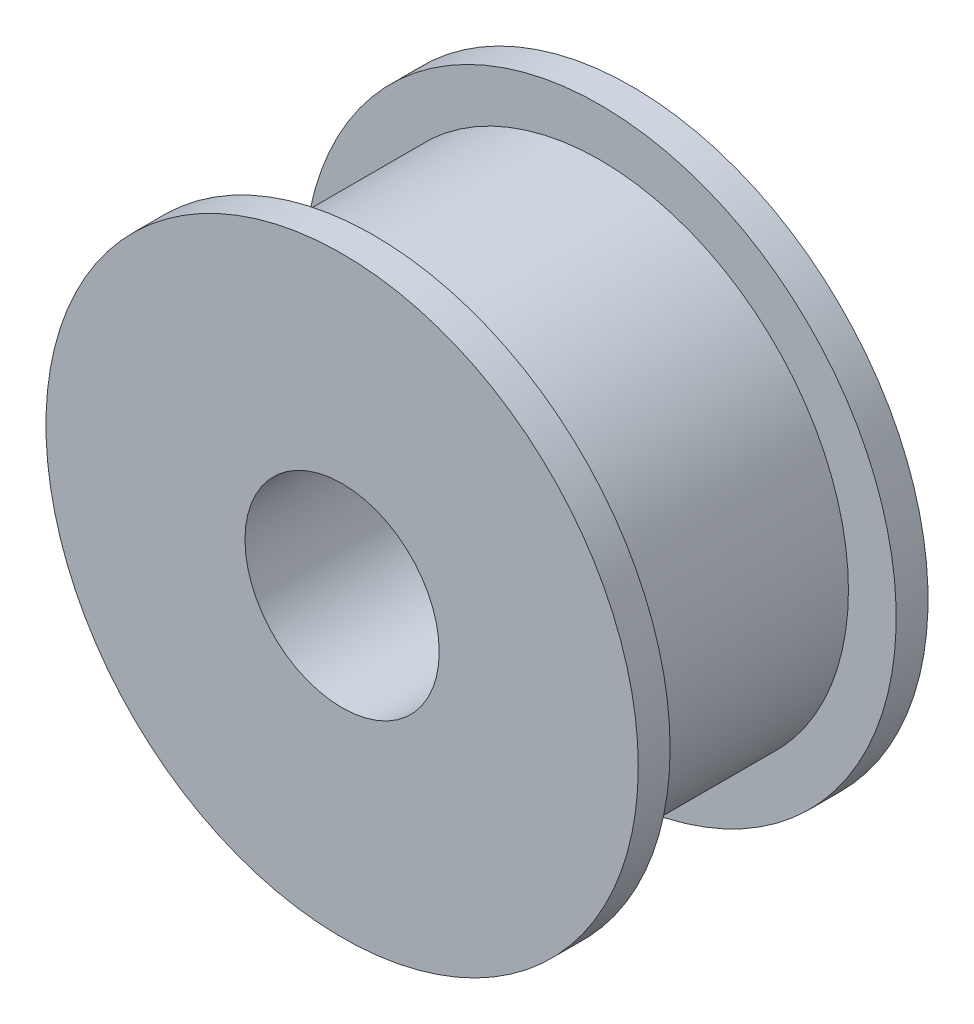
SolidWorks part; units mm, degrees
ref_plane "Plano frontal" through (0, 0, 0) normal (0, 0, 1) x (1, 0, 0)
ref_plane "Plano superior" through (0, 0, 0) normal (0, 1, 0) x (1, 0, 0)
ref_plane "Plano direito" through (0, 0, 0) normal (1, 0, 0) x (0, 0, -1)
sketch "Esboço1" plane through (0, 0, 0) normal (0, 0, 1) x (1, 0, 0)
  circle A0 centre (0, 0) radius 7.8
  circle A1 centre (0, 0) radius 3.05
  dimension "D1" = 6.1
  dimension "D2" = 15.6
extrude "Ressalto-extrusão1" add sketch "Esboço1" along normal blind 9.1
sketch "Esboço2" plane through (0, 0, 0) normal (0, 0, -1) x (-1, 0, 0)
  circle A0 centre (0, 0) radius 9.3
  circle A1 centre (0, 0) radius 7.8 construction
  circle A2 centre (0, 0) radius 7.8
  dimension "D1" = 1.5
extrude "Ressalto-extrusão2" add sketch "Esboço2" against normal blind 1
sketch "Esboço3" plane through (0, 0, 9.1) normal (0, 0, 1) x (1, 0, 0)
  circle A0 centre (0, 0) radius 7.8 construction
  circle A1 centre (0, 0) radius 9.3 construction
  circle A2 centre (0, 0) radius 7.8
  circle A3 centre (0, 0) radius 9.3
extrude "Ressalto-extrusão3" add sketch "Esboço3" against normal blind 1
